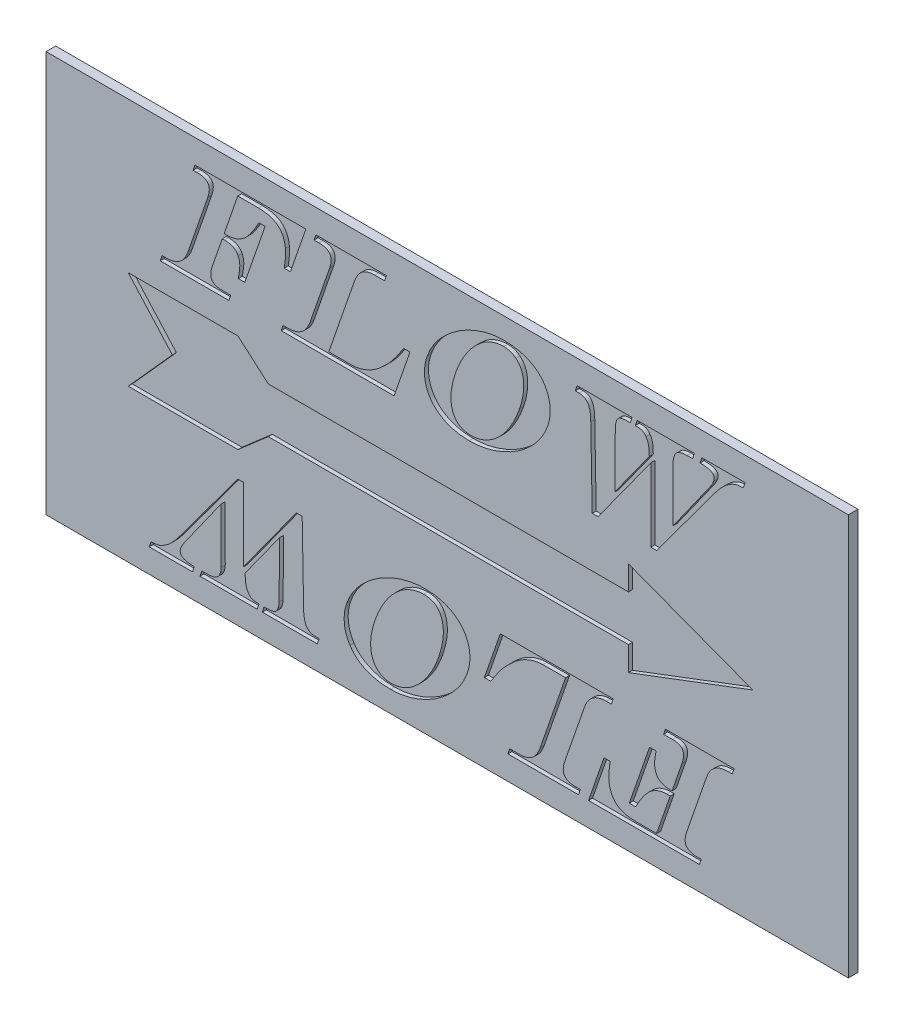
SolidWorks part; units mm, degrees
material "Nickel"
ref_plane "Front Plane" through (0, 0, 0) normal (0, 0, 1) x (1, 0, 0)
ref_plane "Top Plane" through (0, 0, 0) normal (0, 1, 0) x (1, 0, 0)
ref_plane "Right Plane" through (0, 0, 0) normal (1, 0, 0) x (0, 0, -1)
sketch "Sketch1" plane through (0, 0, 0) normal (0, 0, 1) x (1, 0, 0)
  line L1 (25.4, -12.7) -> (-25.4, -12.7)
  line L2 (25.4, -12.7) -> (25.4, 12.7)
  line L3 (25.4, 12.7) -> (-25.4, 12.7)
  line L4 (-25.4, -12.7) -> (-25.4, 12.7)
  line L5 (25.4, -12.7) -> (-25.4, 12.7) construction
  line L6 (25.4, 12.7) -> (-25.4, -12.7) construction
  point P0 (0, 0)
  dimension "D1" = 25.4
  dimension "D2" = 50.8
extrude "Boss-Extrude1" add sketch "Sketch1" along normal blind 0.6096
sketch "Sketch2" plane through (0, 0, 0.6096) normal (0, 0, 1) x (1, 0, 0)
  line L0 (-11.3277, 1.5096) -> (-13.2446, 3.1791)
  line L2 (11.4786, -2.9162) -> (19.3465, 0.0657)
  line L3 (11.4786, 1.5096) -> (-11.3277, 1.5096)
  line L4 (11.4786, -1.3781) -> (11.4786, -2.9162)
  line L5 (11.4786, -1.3781) -> (-11.3277, 1.5096) construction
  line L6 (11.4786, 1.5096) -> (-11.3277, -1.3781) construction
  line L7 (-13.2446, 3.1791) -> (-20.1944, 3.1791)
  line L8 (-20.1944, 3.1791) -> (-17.4011, 0.0657)
  line L9 (11.4786, 1.5096) -> (11.4786, 3.0477)
  line L10 (11.4786, 3.0477) -> (19.3465, 0.0657)
  line L11 (-17.4011, 0.0657) -> (19.3465, 0.0657) construction
  line L12 (11.4786, -1.3781) -> (-11.3277, -1.3781)
  line L13 (-11.3277, -1.3781) -> (-13.2446, -3.0477)
  line L14 (-13.2446, -3.0477) -> (-20.1944, -3.0477)
  line L15 (-20.1944, -3.0477) -> (-17.4011, 0.0657)
  point P0 (0.0755, 0.0657)
extrude "Cut-Extrude1" cut sketch "Sketch2" against normal blind 0.254
sketch "Sketch3" plane through (0, 0, 0.6096) normal (0, 0, 1) x (1, 0, 0)
  text T0 "flow" font "Engravers MT" height 6.35
extrude "Cut-Extrude2" cut sketch "Sketch3" against normal blind 0.254
ref_axis "Axis1" through (0, 0, -0.0305) along (0, 0, 1)
pattern_circular "CirPattern3" count 2 over 360 about axis through (0, 0, -0.0305) along (0, 0, 1) of "Cut-Extrude2"
